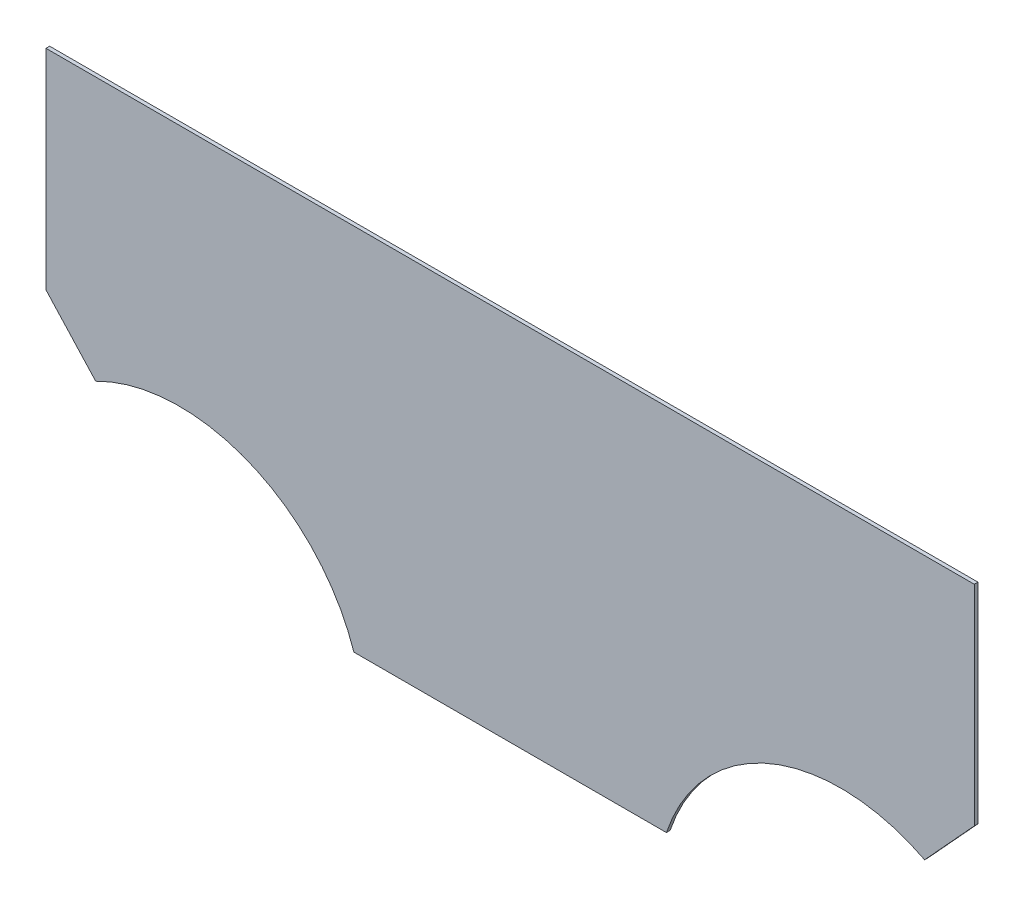
SolidWorks part; units mm, degrees
ref_plane "Front Plane" through (0, 0, 0) normal (0, 0, 1) x (1, 0, 0)
ref_plane "Top Plane" through (0, 0, 0) normal (0, 1, 0) x (1, 0, 0)
ref_plane "Right Plane" through (0, 0, 0) normal (1, 0, 0) x (0, 0, -1)
ref_plane "Plane1" through (0, 0, 0) normal (0, 0, -1) x (-1, 0, 0)
sketch "Sketch1" plane through (0, 0, 0) normal (0, 0, -1) x (-1, 0, 0)
  line L0 (-26.4126, -93.3212) -> (0.6138, -63.8326)
  line L1 (0.6138, -63.8326) -> (0.6138, 50)
  line L2 (0.6138, 50) -> (-504.3862, 50)
  line L3 (-504.3862, 50) -> (-504.3862, -63.8326)
  line L4 (-504.3862, -63.8326) -> (-477.3599, -93.3212)
  line L5 (-336.8862, -150.7282) -> (-166.8862, -150.7282)
  arc A0 (-166.8862, -150.7282) -> (-26.4126, -93.3212) centre (-72.0081, -182.3215) cw
  arc A1 (-477.3599, -93.3212) -> (-336.8862, -150.7282) centre (-431.7644, -182.3215) cw
  dimension "D3" = 170
  dimension "D4" = 505
  dimension "D1" = 100
  dimension "D2" = 100
  dimension "D5" = 167.5
  dimension "D6" = 40
  dimension "D7" = 40
  dimension "D8" = 200.7282
extrude "Boss-Extrude1" add sketch "Sketch1" against normal blind 2
